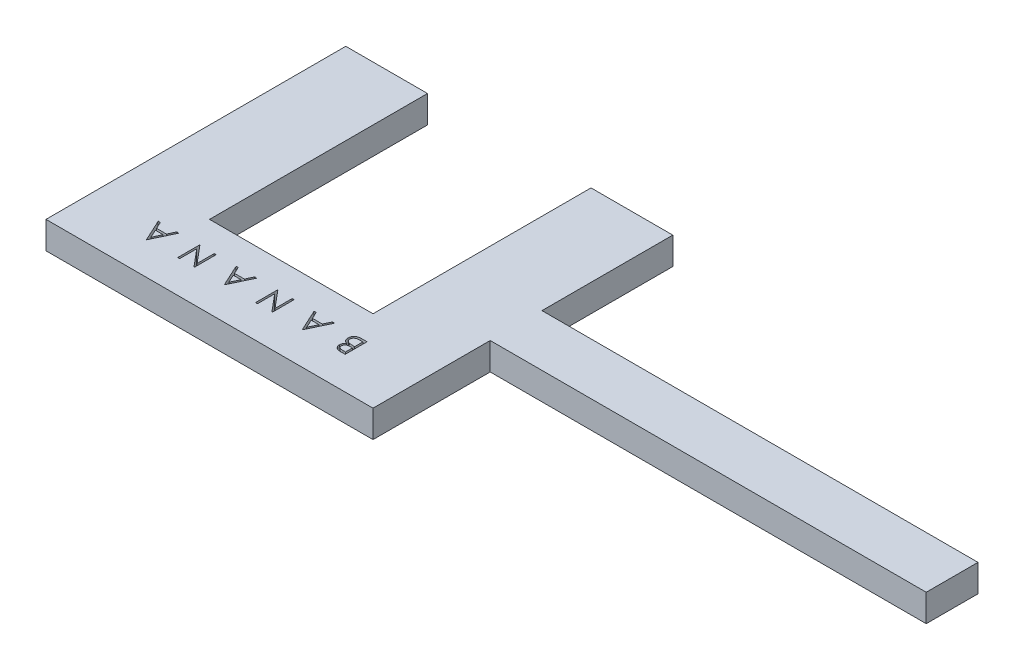
SolidWorks part; units mm, degrees
ref_plane "Front Plane" through (0, 0, 0) normal (0, 0, 1) x (1, 0, 0)
ref_plane "Top Plane" through (0, 0, 0) normal (0, 1, 0) x (1, 0, 0)
ref_plane "Right Plane" through (0, 0, 0) normal (1, 0, 0) x (0, 0, -1)
sketch "Sketch1" plane through (0, 0, 0) normal (0, 1, 0) x (1, 0, 0)
  line L1 (0, -55) -> (60, -55)
  line L2 (60, -55) -> (60, -33.5)
  line L3 (60, -33.5) -> (140, -33.5)
  line L4 (140, -33.5) -> (140, -24)
  line L5 (140, -24) -> (60, -24)
  line L6 (60, -24) -> (60, 0)
  line L7 (0, 0) -> (0, -55)
  line L13 (60, 0) -> (45, 0)
  line L15 (15, 0) -> (15, -40)
  line L16 (15, -40) -> (45, -40)
  line L17 (45, 0) -> (45, -40)
  line L18 (15, 0) -> (0, 0)
  point P4 (0, 0)
  dimension "D1" = 15
  dimension "D2" = 9.5
  dimension "D3" = 15
  dimension "D4" = 140
  dimension "D5" = 60
  dimension "D6" = 15
  dimension "D7" = 55
  dimension "D8" = 24
extrude "Boss-Extrude1" add sketch "Sketch1" along normal blind 5
sketch "Sketch4" plane through (0, 5, 0) normal (0, 1, 0) x (1, 0, 0)
  line L0 (0, -45) -> (60, -45) construction
  line L6 (0, 0) -> (0, -55) construction
  line L7 (60, -55) -> (60, -33.5) construction
  line L9 (45, -40) -> (15, -40) construction
  text T0 "BANANA" font "Century Gothic" height 4
  dimension "D1" = 5
extrude "Cut-Extrude1" cut sketch "Sketch4" against normal blind 3
